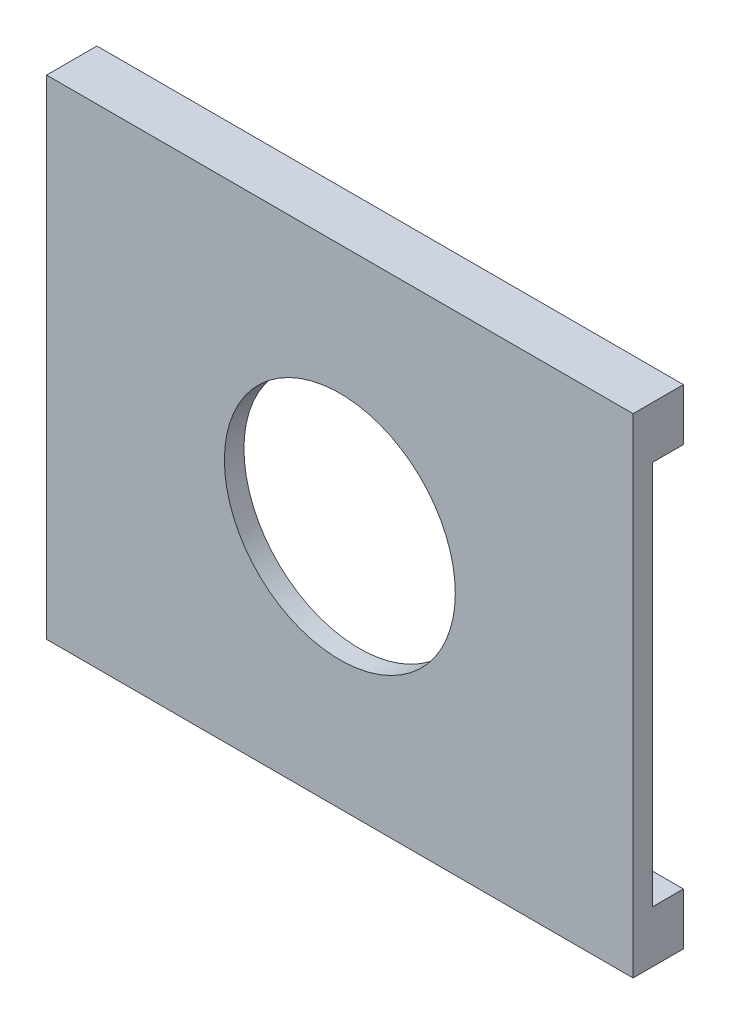
SolidWorks part; units mm, degrees
ref_plane "Front" through (0, 0, 0) normal (0, 0, 1) x (1, 0, 0)
ref_plane "Top" through (0, 0, 0) normal (0, 1, 0) x (1, 0, 0)
ref_plane "Right" through (0, 0, 0) normal (1, 0, 0) x (0, 0, -1)
sketch "Sketch1" plane through (0, 0, 0) normal (0, 0, 1) x (1, 0, 0)
  line L1 (0, 0) -> (76.2, 0)
  line L2 (0, 0) -> (0, 63.5)
  line L3 (0, 63.5) -> (76.2, 63.5)
  line L4 (76.2, 0) -> (76.2, 63.5)
extrude "Boss-Extrude1" add sketch "Sketch1" along normal blind 2.54
ref_plane "Plane1" through (0, 0, 0) normal (0, 0, -1) x (-1, 0, 0)
sketch "Sketch2" plane through (0, 0, 0) normal (0, 0, -1) x (-1, 0, 0)
  line L0 (0, 63.5) -> (0, 56.75)
  line L1 (0, 63.5) -> (0, 0) construction
  line L2 (0, 56.75) -> (-76.2, 56.75)
  line L3 (-76.2, 0) -> (-76.2, 63.5) construction
  line L4 (-76.2, 56.75) -> (-76.2, 63.5)
  line L5 (-76.2, 63.5) -> (0, 63.5)
  line L6 (0, 31.75) -> (-76.2, 31.75) construction
  line L7 (-76.2, 0) -> (0, 0)
  line L8 (-76.2, 6.75) -> (-76.2, 0)
  line L9 (0, 6.75) -> (-76.2, 6.75)
  line L10 (0, 0) -> (0, 6.75)
extrude "Boss-Extrude2" add sketch "Sketch2" along normal blind 4
ref_plane "Plane2" through (0, 0, -4) normal (0, 0, -1) x (-1, 0, 0)
sketch "Sketch3" plane through (0, 0, -4) normal (0, 0, -1) x (-1, 0, 0)
  line L0 (-76.2, 60.125) -> (0, 60.125) construction
  line L1 (-76.2, 63.5) -> (-76.2, 56.75) construction
  line L2 (0, 56.75) -> (0, 63.5) construction
  line L3 (-76.2, 31.75) -> (0, 31.75) construction
  line L4 (-76.2, 6.75) -> (-76.2, 56.75) construction
  line L5 (0, 56.75) -> (0, 6.75) construction
  line L6 (-38.1, 63.5) -> (-38.1, 0) construction
  line L7 (0, 63.5) -> (-76.2, 63.5) construction
  line L8 (-76.2, 0) -> (0, 0) construction
  circle A0 centre (-63.5, 60.125) radius 2.032
  circle A1 centre (-63.5, 3.375) radius 2.032
  circle A2 centre (-12.7, 3.375) radius 2.032
  circle A3 centre (-12.7, 60.125) radius 2.032
extrude "Cut-Extrude1" cut sketch "Sketch3" against normal blind 3.81
ref_plane "Plane3" through (0, 0, 2.54) normal (0, 0, 1) x (1, 0, 0)
sketch "Sketch4" plane through (0, 0, 2.54) normal (0, 0, 1) x (1, 0, 0)
  line L0 (0, 31.75) -> (76.2, 31.75) construction
  line L1 (0, 63.5) -> (0, 0) construction
  line L2 (76.2, 0) -> (76.2, 63.5) construction
  circle A0 centre (38.1, 31.75) radius 15
extrude "Cut-Extrude2" cut sketch "Sketch4" against normal blind 10
